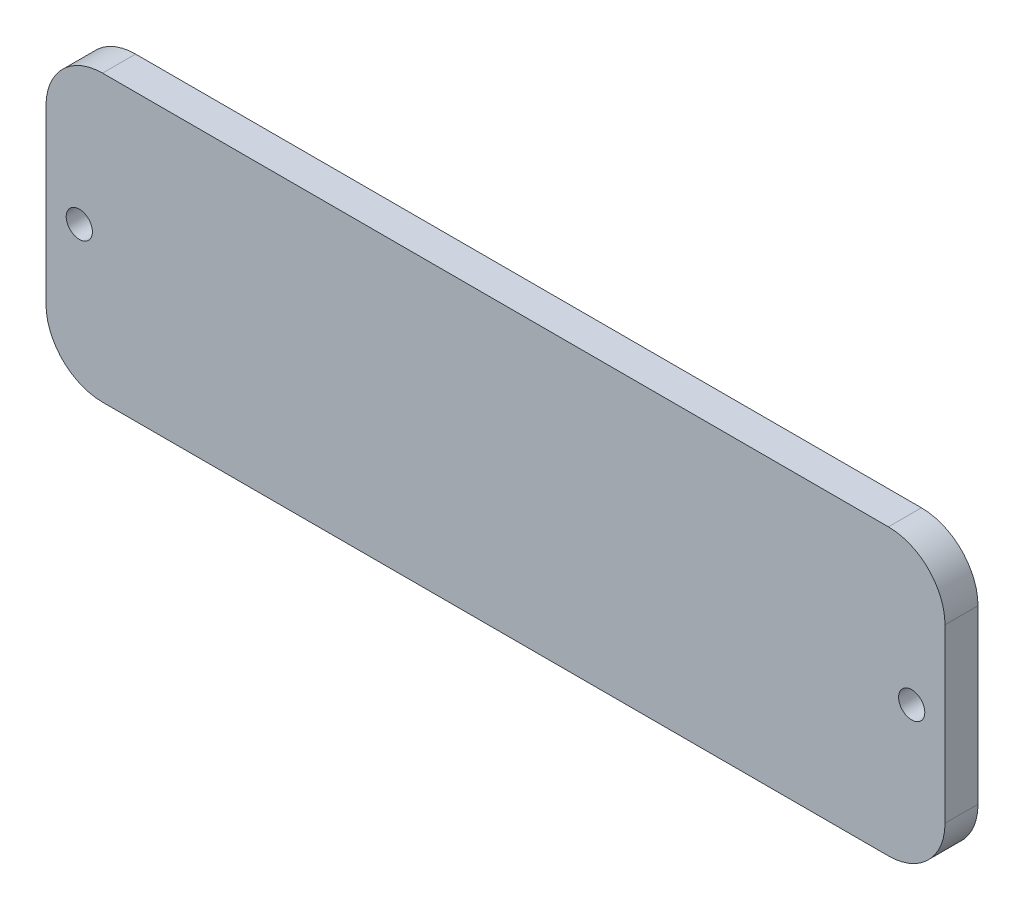
SolidWorks part; units mm, degrees
ref_plane "Front Plane" through (0, 0, 0) normal (0, 0, 1) x (1, 0, 0)
ref_plane "Top Plane" through (0, 0, 0) normal (0, 1, 0) x (1, 0, 0)
ref_plane "Right Plane" through (0, 0, 0) normal (1, 0, 0) x (0, 0, -1)
sketch "Sketch1" plane through (0, 0, -49.2125) normal (0, 0, -1) x (-1, 0, 0)
  line L20 (23.8125, 8.636) -> (-23.8125, 8.636)
  line L21 (-27.2415, 5.207) -> (-27.2415, -5.207)
  line L22 (-23.8125, -8.636) -> (23.8125, -8.636)
  line L23 (27.2415, -5.207) -> (27.2415, 5.207)
  line L24 (23.8125, 8.636) -> (-23.8125, 8.636)
  line L25 (-27.2415, 5.207) -> (-27.2415, -5.207)
  line L26 (-23.8125, -8.636) -> (23.8125, -8.636)
  line L27 (27.2415, -5.207) -> (27.2415, 5.207)
  arc A22 (-23.8125, 8.636) -> (-27.2415, 5.207) centre (-23.8125, 5.207) ccw
  arc A23 (-27.2415, -5.207) -> (-23.8125, -8.636) centre (-23.8125, -5.207) ccw
  arc A24 (23.8125, -8.636) -> (27.2415, -5.207) centre (23.8125, -5.207) ccw
  arc A26 (27.2415, 5.207) -> (23.8125, 8.636) centre (23.8125, 5.207) ccw
  arc A28 (-23.8125, 8.636) -> (-27.2415, 5.207) centre (-23.8125, 5.207) ccw
  arc A30 (-27.2415, -5.207) -> (-23.8125, -8.636) centre (-23.8125, -5.207) ccw
  arc A32 (23.8125, -8.636) -> (27.2415, -5.207) centre (23.8125, -5.207) ccw
  arc A34 (27.2415, 5.207) -> (23.8125, 8.636) centre (23.8125, 5.207) ccw
  dimension "D1" = 0
extrude "Boss-Extrude1" add sketch "Sketch1" against normal blind 2
sketch "Sketch2" plane through (0, 0, -47.2125) normal (0, 0, 1) x (1, 0, 0)
  point P0 (25.223, 0)
  point P1 (-25.223, 0)
hole_wizard "1/16 (0.0625) Diameter Hole2" positions "3DSketch2" profile "Sketch4" hole size "1/16" standard "ANSI Inch"
sketch3d "3DSketch2"
  point P0 (25.223, 0, -47.2125)
  point P2 (-25.223, 0, -47.2125)
sketch "Sketch4" plane through (25.223, 0, -47.2125) normal (1, 0, 0) x (0, -1, 0)
  line L0 (0, 0) -> (0, 19.5269)
  line L1 (0, 19.5269) -> (0.7937, 19.05)
  line L2 (0.7937, 19.05) -> (0.7937, 0)
  line L5 (0.7937, 0) -> (0, 0)
  line L10 (0, 19.5269) -> (-0.7937, 19.05) construction
  line L11 (0, -6.35) -> (0, 107.95) construction
  dimension "Hole Dia." = 1.5875
  dimension "Hole Depth" = 19.05
  dimension "Drill Angle" = 118
